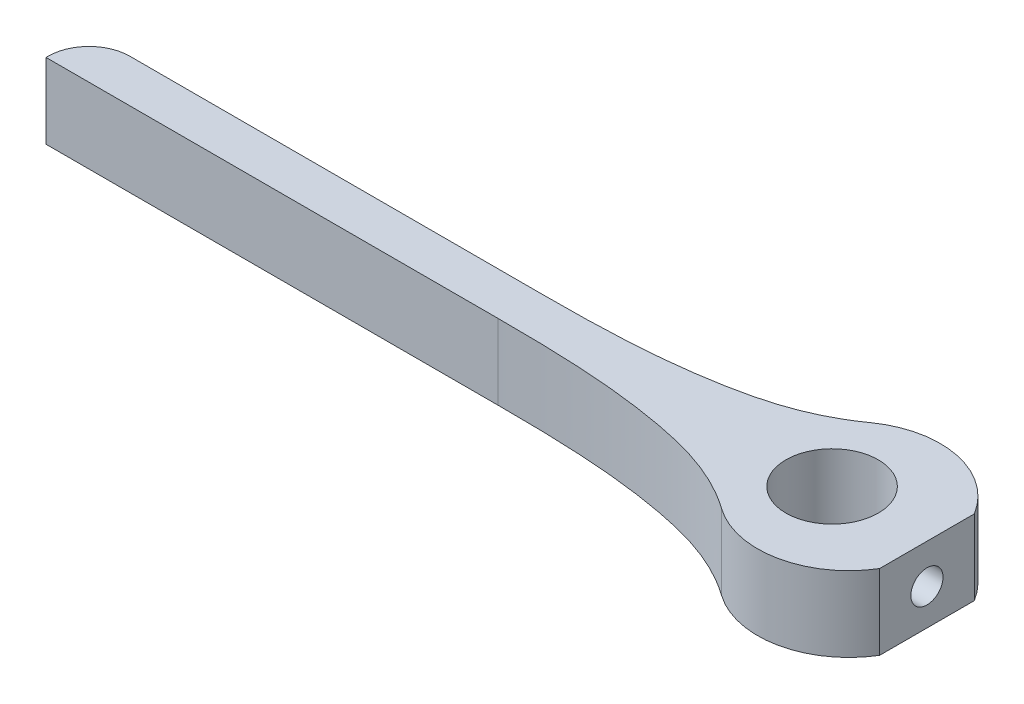
SolidWorks part; units mm, degrees
ref_plane "Front Plane" through (0, 0, 0) normal (0, 0, 1) x (1, 0, 0)
ref_plane "Top Plane" through (0, 0, 0) normal (0, 1, 0) x (1, 0, 0)
ref_plane "Right Plane" through (0, 0, 0) normal (1, 0, 0) x (0, 0, -1)
sketch "Sketch1" plane through (0, 0, 0) normal (0, 1, 0) x (1, 0, 0)
  line L0 (8.8296, -4.4089) -> (8.8296, 4.4089)
  line L1 (-0.8458, 8.719) -> (-6.0644, 5.0049) construction
  line L2 (-71.1704, -2) -> (-29.0824, -2)
  line L3 (-71.1704, -2) -> (-71.1704, -1.8)
  line L4 (-67.3704, 2) -> (-29.0824, 2)
  line L5 (-1.0527, -8.5717) -> (-6.2713, -4.8577) construction
  line L6 (-29.0824, 2) -> (-29.0824, -2) construction
  line L7 (-50.729, 0) -> (-4.3, 0) construction
  circle A0 centre (0, 0) radius 4.3
  arc A1 (8.8296, 4.4089) -> (-3.3662, 6.9252) centre (1.5624, 0) ccw
  arc A2 (-71.1704, -1.8) -> (-67.3704, 2) centre (-67.3704, -1.8) cw
  arc A3 (-3.3662, -6.9252) -> (8.8296, -4.4089) centre (1.5624, 0) ccw
  spline S0 degree 3 poles (-29.0824, 2) (-23.6096, 2) (-15.2454, 2.2386) (-6.6278, 4.604) (-3.3662, 6.9252) knots 0 0 0 0 0.607849 1 1 1 1
  spline S1 degree 3 poles (-29.0824, -2) (-23.6096, -2) (-15.2454, -2.2386) (-6.6278, -4.604) (-3.3662, -6.9252) knots 0 0 0 0 0.607849 1 1 1 1
  point P4 (-29.0824, 0)
  point P19 (-45.3497, -2)
  point P22 (-28.611, 2.0004)
  point P23 (-34.9711, -2)
  point P24 (0, 0)
  dimension "D1" = 3.8
  dimension "D3" = 8.5
  dimension "D4" = 8.5
  dimension "D2" = 4
  dimension "D5" = 80
extrude "Boss-Extrude1" add sketch "Sketch1" along normal blind 7 contours L2 S1 A3 L0 A1 S0 L4 A2 L3 A0
sketch "Sketch2" plane through (8.8296, 0, 0) normal (1, 0, 0) x (0, 0, -1)
  circle A0 centre (0, 3.3587) radius 1.4963
extrude "Cut-Extrude1" cut sketch "Sketch2" against normal up to next
sketch "Sketch3" plane through (8.8296, 0, 0) normal (1, 0, 0) x (0, 0, -1)
  line L1 (-1.6155, 0.5605) -> (1.6155, 0.5605)
  line L2 (1.6155, 0.5605) -> (3.231, 3.3587)
  line L3 (3.231, 3.3587) -> (1.6155, 6.1568)
  line L4 (1.6155, 6.1568) -> (-1.6155, 6.1568)
  line L5 (-1.6155, 6.1568) -> (-3.231, 3.3587)
  line L6 (-3.231, 3.3587) -> (-1.6155, 0.5605)
  circle A0 centre (0, 3.3587) radius 2.7981 construction
  point P1 (0, 0)
  point P10 (-1.5849, 0.5431)
extrude "Cut-Extrude3" cut sketch "Sketch3" along normal blind 4.5 from offset 7
